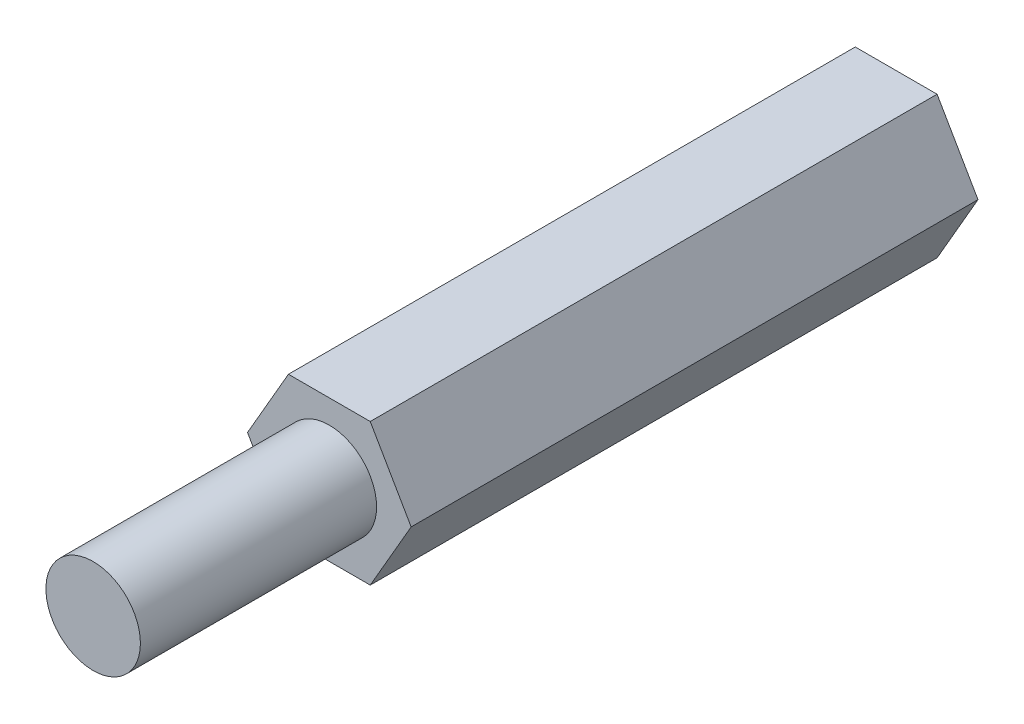
SolidWorks part; units mm, degrees
ref_plane "정면" through (0, 0, 0) normal (0, 0, 1) x (1, 0, 0)
ref_plane "윗면" through (0, 0, 0) normal (0, 1, 0) x (1, 0, 0)
ref_plane "우측면" through (0, 0, 0) normal (1, 0, 0) x (0, 0, -1)
sketch "스케치1" plane through (0, 0, 0) normal (0, 0, 1) x (1, 0, 0)
  line L1 (0.866, -1.5) -> (1.7321, 0)
  line L2 (1.7321, 0) -> (0.866, 1.5)
  line L3 (0.866, 1.5) -> (-0.866, 1.5)
  line L4 (-0.866, 1.5) -> (-1.7321, 0)
  line L5 (-1.7321, 0) -> (-0.866, -1.5)
  line L6 (-0.866, -1.5) -> (0.866, -1.5)
  circle A0 centre (0, 0) radius 1.5 construction
  dimension "D1" = 3
extrude "보스-돌출1" add sketch "스케치1" along normal blind 12
sketch "스케치2" plane through (0, 0, 12) normal (0, 0, 1) x (1, 0, 0)
  circle A0 centre (0, 0) radius 1
  dimension "D1" = 2
extrude "보스-돌출2" add sketch "스케치2" along normal blind 5
sketch "스케치3" plane through (0, 0, 0) normal (0, 0, -1) x (-1, 0, 0)
  point P0 (0, 0)
hole_wizard "M2 여유 구멍1" positions "스케치6" profile "스케치7" hole size "M2" standard "Ansi Metric"
sketch "스케치6" plane through (0, 0, 0) normal (0, 0, -1) x (-1, 0, 0)
  point P0 (0, 0)
sketch "스케치7" plane through (0, 0, 0) normal (1, 0, 0) x (0, 1, 0)
  line L0 (0, 0) -> (0, 3.721)
  line L1 (0, 3.721) -> (1.2, 3)
  line L2 (1.2, 3) -> (1.2, 0)
  line L5 (1.2, 0) -> (0, 0)
  line L10 (0, 3.721) -> (-1.2, 3) construction
  line L11 (0, -6.35) -> (0, 107.95) construction
  dimension "구멍 지름" = 2.4
  dimension "구멍 깊이" = 3
  dimension "드릴 각도" = 118
